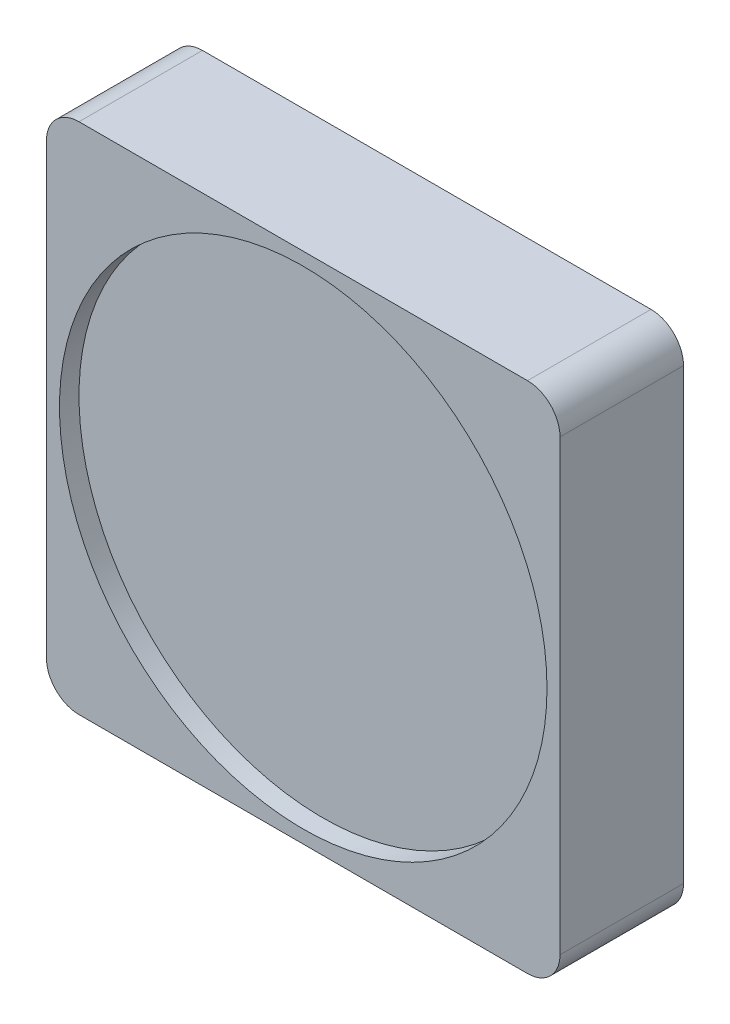
SolidWorks part; units mm, degrees
material "ABS"
ref_plane "Front Plane" through (0, 0, 0) normal (0, 0, 1) x (1, 0, 0)
ref_plane "Top Plane" through (0, 0, 0) normal (0, 1, 0) x (1, 0, 0)
ref_plane "Right Plane" through (0, 0, 0) normal (1, 0, 0) x (0, 0, -1)
sketch "Sketch1" plane through (0, 0, 0) normal (0, 0, 1) x (1, 0, 0)
  line L1 (0, 0) -> (158, 0)
  line L2 (0, 0) -> (0, -158)
  line L3 (0, -158) -> (158, -158)
  line L4 (158, 0) -> (158, -158)
  dimension "D1" = 158
  dimension "D2" = 158
extrude "Boss-Extrude1" add sketch "Sketch1" along normal blind 38
sketch "Sketch2" plane through (0, 0, 38) normal (0, 0, 1) x (1, 0, 0)
  line L0 (158, 0) -> (0, 0) construction
  line L1 (0, 0) -> (0, -158) construction
  circle A0 centre (79, -79) radius 75
  dimension "D1" = 75
  dimension "D2" = 79
  dimension "79" = 79
extrude "Cut-Extrude1" cut sketch "Sketch2" against normal blind 6
fillet "Fillet1" radius 10 4 edges at (158, 0, 19) (158, -158, 19) (0, -158, 19) (0, 0, 19)
